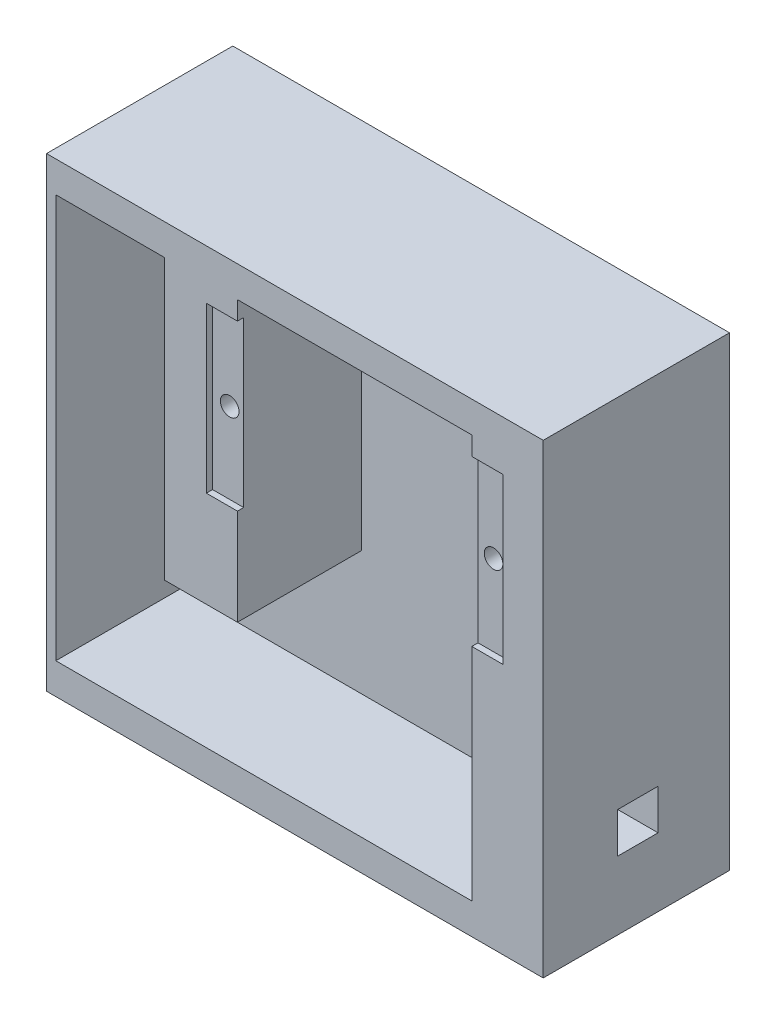
SolidWorks part; units mm, degrees
ref_plane "Front Plane" through (0, 0, 0) normal (0, 0, 1) x (1, 0, 0)
ref_plane "Top Plane" through (0, 0, 0) normal (0, 1, 0) x (1, 0, 0)
ref_plane "Right Plane" through (0, 0, 0) normal (1, 0, 0) x (0, 0, -1)
sketch "Sketch2" plane through (0, 0, 0) normal (0, 0, 1) x (1, 0, 0)
  line L1 (0, 0) -> (-160, 0)
  line L2 (0, 0) -> (0, -150)
  line L3 (0, -150) -> (-160, -150)
  line L4 (-160, 0) -> (-160, -150)
  dimension "D1" = 160
  dimension "D2" = 150
extrude "Boss-Extrude1" add sketch "Sketch2" along normal blind 60
sketch "Sketch3" plane through (0, 0, 60) normal (0, 0, 1) x (1, 0, 0)
  line L0 (0, 0) -> (-160, 0) construction
  line L1 (-98.5, -10) -> (-23, -10)
  line L2 (-98.5, -10) -> (-98.5, -100)
  line L4 (-23, -10) -> (-23, -140)
  line L5 (-157, -140) -> (-23, -140)
  line L6 (-160, -150) -> (0, -150) construction
  line L8 (-160, 0) -> (-160, -150) construction
  line L9 (0, -150) -> (0, 0) construction
  line L10 (-157, -100) -> (-98.5, -100)
  line L11 (-157, -100) -> (-157, -140)
  dimension "D1" = 10
  dimension "D2" = 75.5
  dimension "D3" = 10
  dimension "D4" = 23
  dimension "D5" = 3
  dimension "D7" = 100
extrude "Cut-Extrude1" cut sketch "Sketch3" against normal blind 40
sketch "Sketch4" plane through (0, 0, 60) normal (0, 0, 1) x (1, 0, 0)
  line L1 (0, -150) -> (0, 0) construction
  line L2 (0, 0) -> (-160, 0) construction
  circle A0 centre (-103, -43) radius 3
  circle A1 centre (-18, -43) radius 3
  dimension "D1" = 6
  dimension "D2" = 6
  dimension "D3" = 85
  dimension "D4" = 18
  dimension "D5" = 43
  dimension "D6" = 43
extrude "Cut-Extrude2" cut sketch "Sketch4" against normal up to surface (60 mm away) up to face at (-80, -75, 0)
sketch "Sketch5" plane through (0, 0, 0) normal (1, 0, 0) x (0, 0, -1)
  line L0 (-60, -150) -> (0, -150) construction
  line L1 (-36, -115) -> (-23, -115)
  line L2 (-36, -115) -> (-36, -128)
  line L3 (-36, -128) -> (-23, -128)
  line L4 (-23, -115) -> (-23, -128)
  line L5 (0, -150) -> (0, 0) construction
  point P4 (-29.5, -128)
  dimension "D1" = 22
  dimension "D2" = 13
  dimension "D3" = 13
  dimension "D4" = 23
extrude "Cut-Extrude3" cut sketch "Sketch5" against normal blind 50
sketch "Sketch6" plane through (0, 0, 60) normal (0, 0, 1) x (1, 0, 0)
  line L0 (-98.5, -10) -> (-98.5, -100) construction
  line L1 (-108.5, -16) -> (-98.5, -16)
  line L2 (-108.5, -16) -> (-108.5, -69)
  line L3 (-108.5, -69) -> (-98.5, -69)
  line L4 (-98.5, -16) -> (-98.5, -69)
  line L5 (-23, -140) -> (-23, -10) construction
  line L6 (-23, -16) -> (-13, -16)
  line L7 (-23, -16) -> (-23, -69)
  line L8 (-23, -69) -> (-13, -69)
  line L9 (-13, -16) -> (-13, -69)
  line L10 (0, 0) -> (-160, 0) construction
  point P12 (-103.5, -16)
  dimension "D1" = 53
  dimension "D2" = 53
  dimension "D3" = 16
  dimension "D4" = 16
  dimension "D5" = 10
  dimension "D6" = 10
extrude "Cut-Extrude4" cut sketch "Sketch6" against normal blind 2
sketch "Sketch7" plane through (0, 0, 60) normal (0, 0, 1) x (1, 0, 0)
  line L0 (0, 0) -> (-160, 0) construction
  line L1 (-157, -10) -> (-122, -10)
  line L2 (-157, -10) -> (-157, -140)
  line L3 (-157, -140) -> (-122, -140)
  line L4 (-122, -10) -> (-122, -140)
  line L5 (-160, 0) -> (-160, -150) construction
  line L7 (-160, -150) -> (0, -150) construction
  dimension "D1" = 10
  dimension "D2" = 35
  dimension "D3" = 3
  dimension "D4" = 10
extrude "Cut-Extrude5" cut sketch "Sketch7" against normal blind 40
